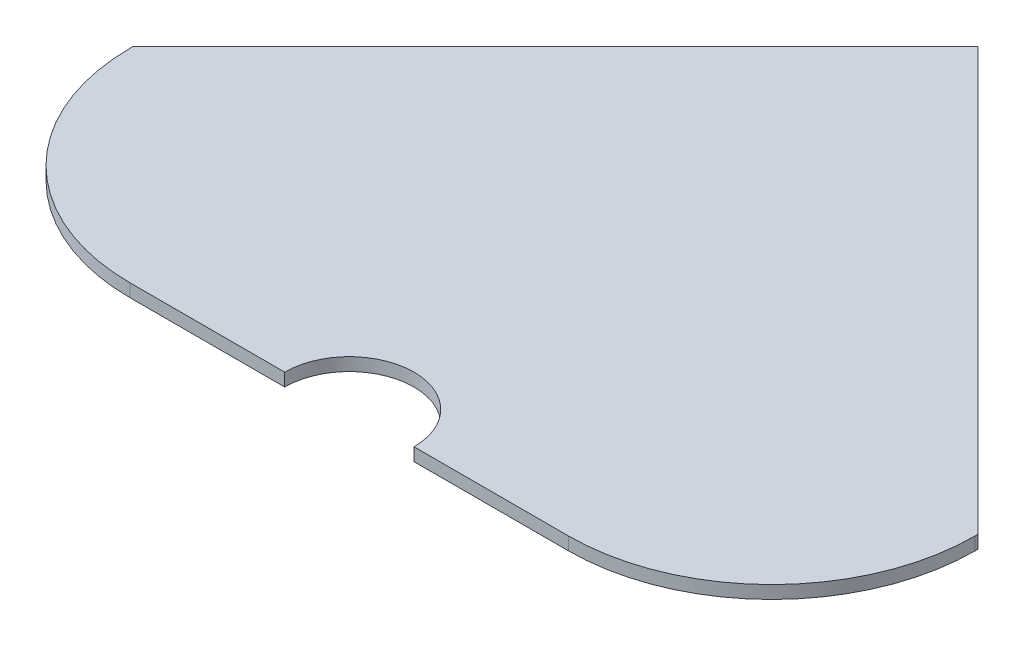
SolidWorks part; units mm, degrees
material "plexiglas"
ref_plane "Front Plane" through (0, 0, 0) normal (0, 0, 1) x (1, 0, 0)
ref_plane "Top Plane" through (0, 0, 0) normal (0, 1, 0) x (1, 0, 0)
ref_plane "Right Plane" through (0, 0, 0) normal (1, 0, 0) x (0, 0, -1)
sketch "basis_deksel_schets" plane through (0, 0, 0) normal (0, 1, 0) x (1, 0, 0)
  line L0 (-98, 23.925) -> (0, 121.925)
  line L1 (-50.85, -23.925) -> (50.85, -23.925)
  line L2 (-98, 23.225) -> (-98, 23.925)
  line L4 (98, 23.225) -> (98, 23.925)
  line L5 (-98, -23.925) -> (98, 23.925) construction
  line L6 (-98, 23.925) -> (98, -23.925) construction
  line L7 (0, 121.925) -> (98, 23.925)
  line L8 (-98, 23.925) -> (98, 23.925) construction
  line L9 (0, 23.925) -> (0, 121.925) construction
  arc A0 (50.85, -23.925) -> (98, 23.225) centre (50.85, 23.225) ccw
  arc A1 (-50.85, -23.925) -> (-98, 23.225) centre (-50.85, 23.225) cw
  point P0 (0, 0)
  dimension "D6" = 47.15
  dimension "D1" = 47.85
  dimension "D2" = 196
  dimension "D3" = 47.85
  dimension "D4" = 90
  dimension "D5" = 145.85
extrude "basis_deksel" add sketch "basis_deksel_schets" along normal blind 3
sketch "uitsparing_schets" plane through (0, 3, 0) normal (0, 1, 0) x (1, 0, 0)
  line L0 (-50.85, -23.925) -> (50.85, -23.925) construction
  line L1 (-15, -23.925) -> (15, -23.925)
  arc A0 (-15, -23.925) -> (15, -23.925) centre (0, -23.925) cw
  dimension "D1" = 15
extrude "uitsparing" cut sketch "uitsparing_schets" against normal through all
